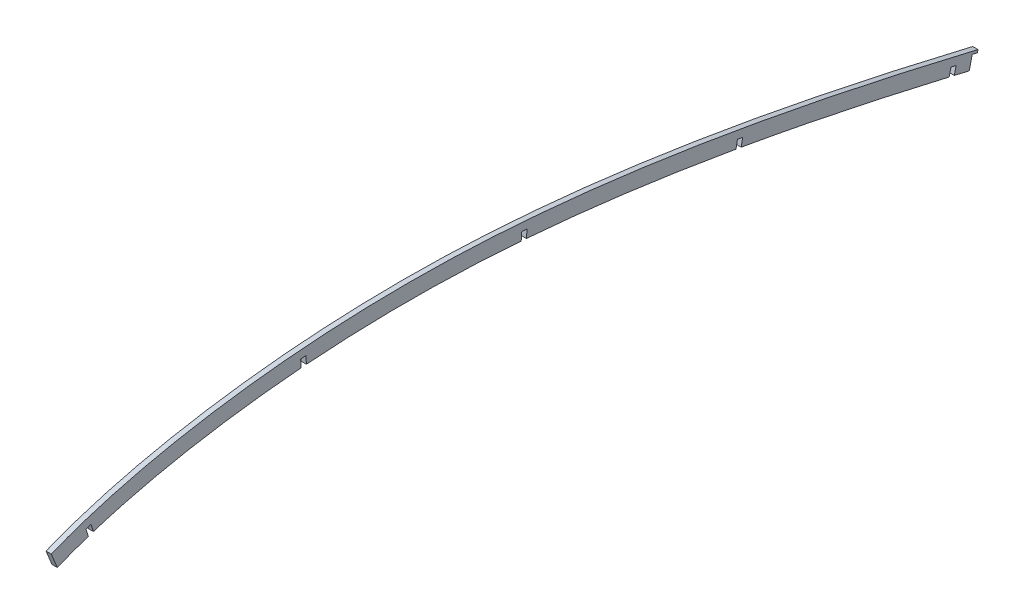
SolidWorks part; units mm, degrees
material "Balsa"
ref_plane "Front" through (0, 0, 0) normal (0, 0, 1) x (1, 0, 0)
ref_plane "Top" through (0, 0, 0) normal (0, 1, 0) x (1, 0, 0)
ref_plane "Right" through (0, 0, 0) normal (1, 0, 0) x (0, 0, -1)
sketch "Sketch1" plane through (0, 0, 0) normal (1, 0, 0) x (0, 0, -1)
  line L0 (58.3503, 42.3126) -> (61.9608, 33.4984)
  line L1 (617.2963, 26.4036) -> (615.0816, 17.1396)
  line L2 (78.8208, 51.4601) -> (121.5265, -80.0182) construction
  line L3 (78.8208, 51.4601) -> (121.5265, -80.0182) construction
  line L4 (221.241, -68.7131) -> (209.8123, 75.4717) construction
  line L5 (221.241, -68.7131) -> (209.8123, 75.4717) construction
  line L6 (344.2165, 75.0826) -> (333.6085, -60.2798) construction
  line L7 (344.2165, 75.0826) -> (333.6085, -60.2798) construction
  line L8 (474.8438, 58.0051) -> (472.6476, 45.4964) construction
  line L9 (474.8438, 58.0051) -> (468.1916, 20.1163) construction
  line L10 (603.9897, 31.1863) -> (568.0177, -122.1933) construction
  line L11 (603.9897, 31.1863) -> (568.0177, -122.1933) construction
  line L12 (79.3112, 49.9502) -> (82.2531, 40.8909) construction
  line L13 (82.292, 45.9108) -> (79.2723, 44.9302)
  line L14 (82.292, 45.9108) -> (83.7434, 41.371)
  line L15 (79.2723, 44.9302) -> (80.7655, 40.404)
  line L16 (209.9378, 73.8885) -> (210.6909, 64.3933) construction
  line L17 (211.8969, 69.2664) -> (208.7318, 69.0154)
  line L18 (211.8969, 69.2664) -> (212.2634, 64.5163)
  line L19 (208.7318, 69.0154) -> (209.1186, 64.2669)
  line L20 (344.0924, 73.4996) -> (343.3486, 64.0037) construction
  line L21 (345.3031, 68.6277) -> (342.1378, 68.8756)
  line L22 (345.3031, 68.6277) -> (344.924, 63.8791)
  line L23 (342.1378, 68.8756) -> (341.773, 64.1259)
  line L24 (474.5693, 56.4417) -> (472.9222, 47.0602) construction
  line L25 (475.3093, 51.4764) -> (472.1822, 52.0254)
  line L26 (475.3093, 51.4764) -> (474.4815, 46.7857)
  line L27 (472.1822, 52.0254) -> (471.3627, 47.3332)
  line L28 (603.6272, 29.6408) -> (601.4522, 20.3675) construction
  line L29 (604.0853, 24.6416) -> (600.9942, 25.3666)
  line L30 (604.0853, 24.6416) -> (602.9954, 20.0051)
  line L31 (600.9942, 25.3666) -> (599.9089, 20.729)
  line L32 (616.9272, 24.8596) -> (613.8392, 25.5978)
  line L33 (613.8392, 25.5978) -> (611.9932, 17.8764)
  spline S0 degree 3 poles (3042.8982, 1190.4581) (2013.7173, -569.2988) (1339.2811, -143.9365) (590.1275, 32.8296) (554.428, 40.9139) (503.6861, 51.3186) (452.3926, 60.4658) (400.8435, 67.985) (357.6791, 72.5891) (323.0562, 75.0503) (288.383, 76.5084) (253.6666, 76.4258) (219.01, 74.7031) (193.0823, 72.5122) (167.2461, 69.4104) (141.5489, 65.3542) (116.056, 60.2087) (95.0651, 54.851) (78.5123, 49.7753) (68.6761, 46.3495) (-137.5654, -32.7885) (-235.9417, -353.7464) (1003.3904, -2762.3014) knots -2.456761 -2.456761 -2.456761 -2.456761 0.243308 0.25112 0.3125 0.375 0.4375 0.5 0.5625 0.59375 0.625 0.6875 0.71875 0.75 0.78125 0.8125 0.84375 0.875 0.890625 0.90625 0.912624 1.689259 1.689259 1.689259 1.689259 only from (617.2963, 26.4036) to (58.3503, 42.3126) construction
  spline S1 degree 3 poles (617.2963, 26.4036) (615.1843, 26.9085) (610.9593, 27.9143) (590.1275, 32.8296) (554.428, 40.9139) (503.6861, 51.3186) (452.3926, 60.4658) (400.8435, 67.985) (357.6791, 72.5891) (323.0562, 75.0503) (288.383, 76.5084) (253.6666, 76.4258) (219.01, 74.7031) (193.0823, 72.5122) (167.2461, 69.4104) (141.5489, 65.3542) (116.056, 60.2087) (95.0651, 54.851) (78.5123, 49.7753) (68.6761, 46.3495) (61.9863, 43.7825) (59.3495, 42.7219) (58.3503, 42.3126) knots 0.235495 0.235495 0.235495 0.235495 0.243308 0.25112 0.3125 0.375 0.4375 0.5 0.5625 0.59375 0.625 0.6875 0.71875 0.75 0.78125 0.8125 0.84375 0.875 0.890625 0.90625 0.912624 0.91653 0.91653 0.91653 0.91653
  spline S2 degree 1 poles (615.0816, 17.1396) (61.9608, 33.4984) knots 0 0 1 1 construction
  spline S3 degree 3 poles (615.0816, 17.1396) (614.31, 17.3241) (613.0227, 17.6314) (610.4297, 18.2487) (607.3017, 18.9906) (604.431, 19.6677) (602.7382, 20.0656) (602.2238, 20.1864) (601.7094, 20.3071) (601.195, 20.4278) (600.6806, 20.5484) (600.1661, 20.6688) (581.9991, 24.9202) (540.9192, 34.1507) (499.3033, 42.3857) (475.244, 46.6511) (474.2217, 46.8316) (473.7019, 46.9231) (473.1821, 47.0145) (472.6623, 47.1058) (472.1425, 47.1969) (471.6226, 47.2879) (449.9896, 51.066) (416.8168, 56.2328) (374.872, 61.2164) (353.996, 63.1548) (344.6614, 63.9001) (344.1363, 63.9417) (343.6111, 63.9831) (343.086, 64.0243) (342.5608, 64.0651) (342.0356, 64.1057) (340.2178, 64.2454) (326.8551, 65.2353) (302.0845, 66.5731) (267.0199, 67.0295) (237.1914, 66.1868) (218.8368, 65.0236) (212.0013, 64.4962) (211.4771, 64.4553) (210.9529, 64.4141) (210.4288, 64.3726) (209.9047, 64.3306) (209.3806, 64.2883) (205.1145, 63.9408) (189.3689, 62.5257) (162.3558, 59.2266) (133.7105, 54.219) (111.101, 49.1353) (96.4575, 45.2694) (87.2715, 42.499) (83.4947, 41.2916) (82.9978, 41.1318) (82.5012, 40.9715) (82.0049, 40.8104) (81.5089, 40.6483) (81.0131, 40.4857) (79.8293, 40.0952) (76.0583, 38.8298) (69.8711, 36.6322) (64.5884, 34.5748) (61.9608, 33.4984) knots 0.235495 0.235495 0.235495 0.235495 0.238359 0.240268 0.245113 0.249958 0.250911 0.251388 0.251864 0.252818 0.253294 0.253771 0.254724 0.320624 0.405754 0.408078 0.409032 0.40951 0.409987 0.410942 0.411419 0.411897 0.412852 0.490883 0.533448 0.566036 0.566994 0.567472 0.567951 0.568908 0.569386 0.569865 0.570822 0.576012 0.618577 0.661142 0.703707 0.72729 0.72825 0.728729 0.729209 0.730169 0.730648 0.731128 0.732088 0.746271 0.788836 0.831401 0.852683 0.873965 0.887226 0.888194 0.888678 0.889163 0.890131 0.890616 0.891101 0.892069 0.895248 0.905889 0.91653 0.91653 0.91653 0.91653
  point P20 (80.7822, 45.4205)
  point P28 (210.3143, 69.1409)
  point P35 (343.7205, 68.7516)
  point P39 (611.6825, 17.9504)
  point P47 (473.7458, 51.7509)
  point P54 (602.5397, 25.0041)
  dimension "D2" = 3.175
  dimension "D3" = 3.175
  dimension "D4" = 3.175
  dimension "D5" = 3.175
  dimension "D6" = 3.175
  dimension "D7" = 3.175
  dimension "D8" = 1.5875
  dimension "D1" = 9.525
extrude "Boss-Extrude2" add sketch "Sketch1" along normal blind 3.175 from offset 1.5875 contours S3 L1 S1 L0 L15 L13 L14 L19 L17 L18 L23 L21 L22 L27 L25 L26 L31 L29 L30
